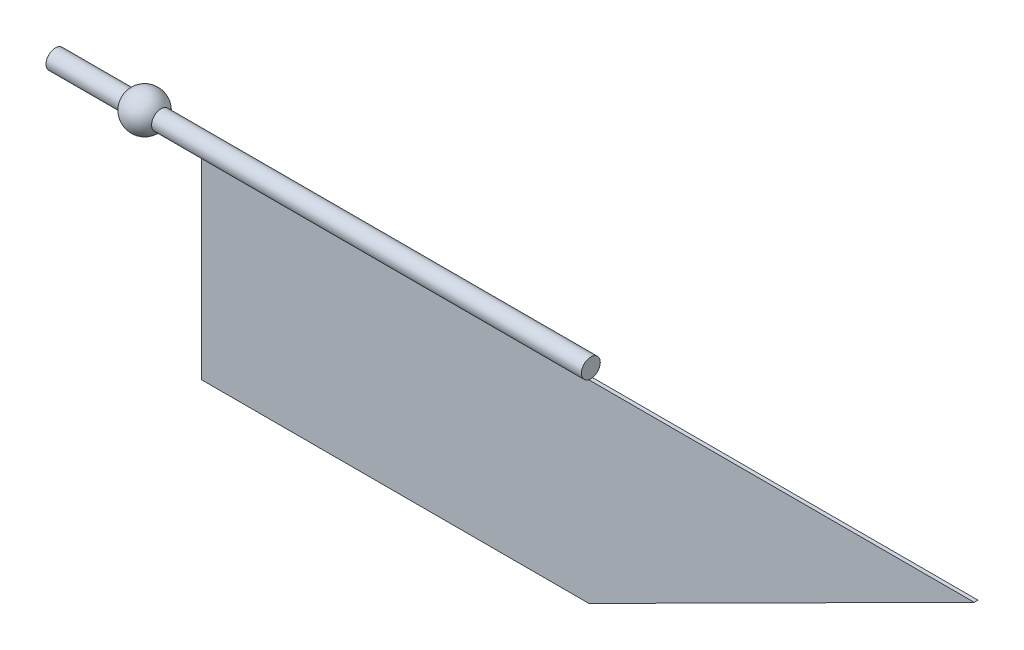
SolidWorks part; units mm, degrees
ref_plane "Front Plane" through (0, 0, 0) normal (0, 0, 1) x (1, 0, 0)
ref_plane "Top Plane" through (0, 0, 0) normal (0, 1, 0) x (1, 0, 0)
ref_plane "Right Plane" through (0, 0, 0) normal (1, 0, 0) x (0, 0, -1)
sketch "Sketch1" plane through (0, 0, 0) normal (0, 0, 1) x (1, 0, 0)
  line L0 (0, 0) -> (35.9365, 0)
  line L1 (35.9365, 0) -> (35.9365, 0.635)
  line L2 (35.9365, 0.635) -> (0, 0.635)
  line L3 (0, 0.635) -> (0, 0)
  arc A1 (7.2567, 0.635) -> (4.7167, 0.635) centre (5.9867, 0.635) cw
  point P4 (10.0505, 1.27)
  point P6 (7.4255, 1.27)
  point P7 (8.1489, 3.81)
  point P11 (7.621, 1.5607)
  point P12 (4.4655, 1.27)
  point P13 (5.9867, 1.27)
  dimension "D2" = 1.27
  dimension "D1" = 0.635
revolve "Revolve1" add sketch "Sketch1" angle 360 about L2
sketch "Sketch2" plane through (0, 0, 0) normal (0, 0, 1) x (1, 0, 0)
  line L0 (9.9212, 0) -> (9.9212, -12.9977)
  line L1 (7.0865, 0) -> (35.9365, 0) construction
  line L2 (9.9212, -12.9977) -> (35.9365, -12.9977)
  line L3 (35.9365, -12.9977) -> (35.9365, 0)
  line L4 (9.9212, 0) -> (35.9365, 0)
  line L5 (35.9365, -12.9977) -> (61.8003, 0)
  line L6 (61.8003, 0) -> (35.9365, 0)
extrude "Boss-Extrude1" add sketch "Sketch2" along normal mid plane 0.254 separate body contours L5 L6 L3 | L4 L0 L2 L3
